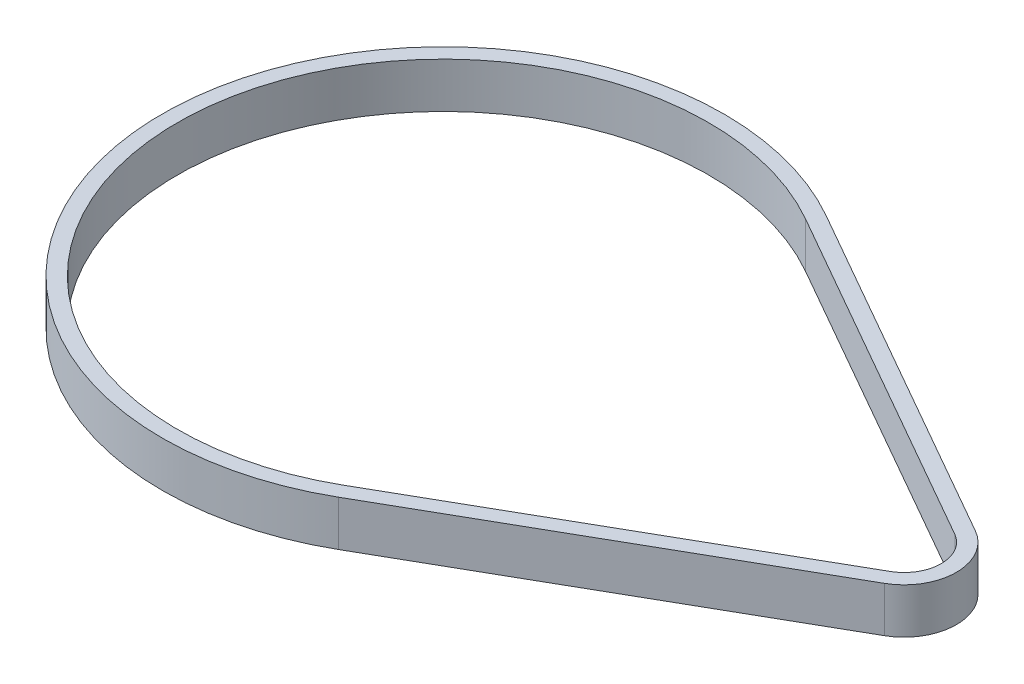
SolidWorks part; units mm, degrees
ref_plane "Front Plane" through (0, 0, 0) normal (0, 0, 1) x (1, 0, 0)
ref_plane "Top Plane" through (0, 0, 0) normal (0, 1, 0) x (1, 0, 0)
ref_plane "Right Plane" through (0, 0, 0) normal (1, 0, 0) x (0, 0, -1)
sketch "Sketch1" plane through (0, 0, 0) normal (0, 1, 0) x (1, 0, 0)
  line L0 (-44.2539, 0) -> (44.2539, 0) construction
  line L1 (-200.915, -30.5284) -> (-154.9011, -4.2688)
  line L2 (-154.9011, 4.2688) -> (-200.915, 30.5284)
  line L3 (-199.9237, -32.2655) -> (-153.9098, -6.0058)
  line L4 (-153.9098, 6.0058) -> (-199.9237, 32.2655)
  arc A0 (-200.915, 30.5284) -> (-200.915, -30.5284) centre (-218.3373, 0) ccw
  arc A1 (-154.9011, 4.2688) -> (-154.9011, -4.2688) centre (-157.3373, 0) cw
  arc A2 (-199.9237, 32.2655) -> (-199.9237, -32.2655) centre (-218.3373, 0) ccw
  arc A3 (-153.9098, 6.0058) -> (-153.9098, -6.0058) centre (-157.3373, 0) cw
  dimension "D1" = 35.15
  dimension "D2" = 4.915
  dimension "D3" = 61
  dimension "D4" = 2
extrude "Boss-Extrude1" add sketch "Sketch1" along normal blind 6
